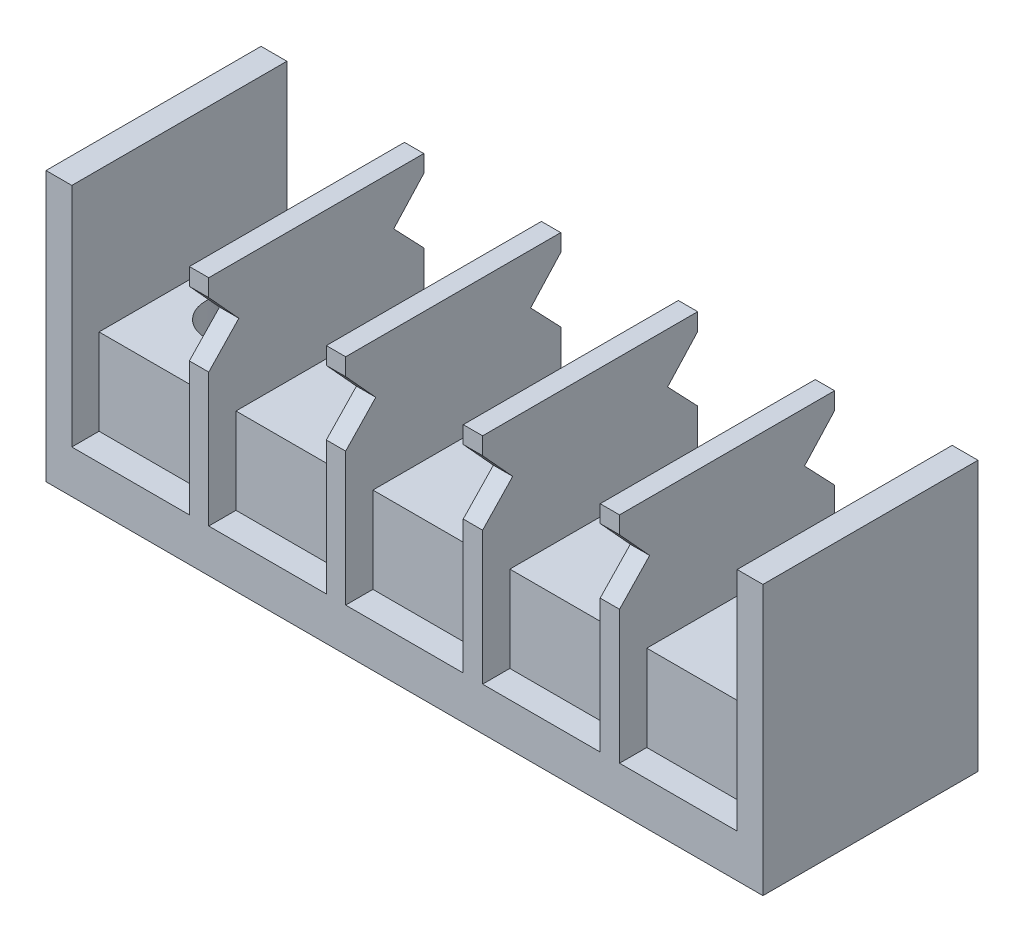
SolidWorks part; units mm, degrees
ref_plane "前视基准面" through (0, 0, 0) normal (0, 0, 1) x (1, 0, 0)
ref_plane "上视基准面" through (0, 0, 0) normal (0, 1, 0) x (1, 0, 0)
ref_plane "右视基准面" through (0, 0, 0) normal (1, 0, 0) x (0, 0, -1)
sketch "草图1" plane through (0, 0, 0) normal (0, 1, 0) x (1, 0, 0)
  line L0 (0, 12.7565) -> (0, -11.1323) construction
  line L1 (-25, -7.5) -> (25, -7.5)
  line L2 (-25, -7.5) -> (-25, 7.5)
  line L3 (-25, 7.5) -> (25, 7.5)
  line L4 (25, -7.5) -> (25, 7.5)
  line L5 (-29.1602, 0) -> (32.7116, 0) construction
  dimension "D1" = 50
  dimension "D2" = 15
extrude "拉伸1" add sketch "草图1" along normal blind 18.8
sketch "草图2" plane through (0, 18.8, 0) normal (0, 1, 0) x (-1, 0, 0)
  line L0 (-25, -7.5) -> (25, -7.5) construction
  line L1 (-23.2, -7.5) -> (23.2, -7.5)
  line L2 (-23.2, -7.5) -> (-23.2, 7.5)
  line L3 (-23.2, 7.5) -> (23.2, 7.5)
  line L4 (23.2, -7.5) -> (23.2, 7.5)
  line L5 (25, 7.5) -> (-25, 7.5) construction
  line L6 (-25, 7.5) -> (-25, -7.5) construction
  line L7 (25, -7.5) -> (25, 7.5) construction
  dimension "D1" = 1.8
  dimension "D2" = 1.8
extrude "切除-拉伸1" cut sketch "草图2" against normal offset from surface (0.8 mm away) 18 up to face at (0, 0, 0)
sketch "草图4" plane through (0, 18, 0) normal (0, 1, 0) x (-1, 0, 0)
  line L0 (23.2, 7.5) -> (-23.2, 7.5) construction
  line L1 (-23.2, -7.5) -> (-15, -7.5)
  line L2 (-23.2, -7.5) -> (-23.2, 7.5)
  line L3 (-23.2, 7.5) -> (-15, 7.5)
  line L4 (-15, -7.5) -> (-15, 7.5)
  line L5 (-13.65, -7.5) -> (-5.45, -7.5)
  line L6 (-13.65, -7.5) -> (-13.65, 7.5)
  line L7 (-13.65, 7.5) -> (-5.45, 7.5)
  line L8 (-5.45, -7.5) -> (-5.45, 7.5)
  line L9 (-4.1, -7.5) -> (4.1, -7.5)
  line L10 (-4.1, -7.5) -> (-4.1, 7.5)
  line L11 (-4.1, 7.5) -> (4.1, 7.5)
  line L12 (4.1, -7.5) -> (4.1, 7.5)
  line L13 (5.45, -7.5) -> (13.65, -7.5)
  line L14 (5.45, -7.5) -> (5.45, 7.5)
  line L15 (5.45, 7.5) -> (13.65, 7.5)
  line L16 (13.65, -7.5) -> (13.65, 7.5)
  line L17 (15, -7.5) -> (23.2, -7.5)
  line L18 (15, -7.5) -> (15, 7.5)
  line L19 (15, 7.5) -> (23.2, 7.5)
  line L20 (23.2, -7.5) -> (23.2, 7.5)
  dimension "D1" = 8.2
extrude "切除-拉伸2" cut sketch "草图4" against normal offset from surface (9 mm away) 9 up to face at (0, 0, 0)
sketch "草图5" plane through (0, 18, 0) normal (0, 1, 0) x (-1, 0, 0)
  line L0 (15, 7.5) -> (15, -7.5) construction
  line L1 (23.2, -7.5) -> (15, -7.5)
  line L2 (23.2, -7.5) -> (23.2, -5.6)
  line L3 (23.2, -5.6) -> (15, -5.6)
  line L4 (15, -7.5) -> (15, -5.6)
  line L5 (29.9336, 0) -> (-26.6321, 0) construction
  line L6 (15, 7.5) -> (15, 5.6)
  line L7 (23.2, 5.6) -> (15, 5.6)
  line L8 (23.2, 7.5) -> (23.2, 5.6)
  line L9 (23.2, 7.5) -> (15, 7.5)
  line L10 (13.65, -7.5) -> (5.45, -7.5)
  line L11 (13.65, -7.5) -> (13.65, -5.6)
  line L12 (13.65, -5.6) -> (5.45, -5.6)
  line L13 (5.45, -7.5) -> (5.45, -5.6)
  line L14 (5.45, 7.5) -> (5.45, 5.6)
  line L15 (13.65, 5.6) -> (5.45, 5.6)
  line L16 (13.65, 7.5) -> (13.65, 5.6)
  line L17 (13.65, 7.5) -> (5.45, 7.5)
  line L18 (4.1, -7.5) -> (-4.1, -7.5)
  line L19 (4.1, -7.5) -> (4.1, -5.6)
  line L20 (4.1, -5.6) -> (-4.1, -5.6)
  line L21 (-4.1, -7.5) -> (-4.1, -5.6)
  line L22 (-4.1, 7.5) -> (-4.1, 5.6)
  line L23 (4.1, 5.6) -> (-4.1, 5.6)
  line L24 (4.1, 7.5) -> (4.1, 5.6)
  line L25 (4.1, 7.5) -> (-4.1, 7.5)
  line L26 (-5.45, -7.5) -> (-13.65, -7.5)
  line L27 (-5.45, -7.5) -> (-5.45, -5.6)
  line L28 (-5.45, -5.6) -> (-13.65, -5.6)
  line L29 (-13.65, -7.5) -> (-13.65, -5.6)
  line L30 (-13.65, 7.5) -> (-13.65, 5.6)
  line L31 (-5.45, 5.6) -> (-13.65, 5.6)
  line L32 (-5.45, 7.5) -> (-5.45, 5.6)
  line L33 (-5.45, 7.5) -> (-13.65, 7.5)
  line L34 (-15, -7.5) -> (-23.2, -7.5)
  line L35 (-15, -7.5) -> (-15, -5.6)
  line L36 (-15, -5.6) -> (-23.2, -5.6)
  line L37 (-23.2, -7.5) -> (-23.2, -5.6)
  line L38 (-23.2, 7.5) -> (-23.2, 5.6)
  line L39 (-15, 5.6) -> (-23.2, 5.6)
  line L40 (-15, 7.5) -> (-15, 5.6)
  line L41 (-15, 7.5) -> (-23.2, 7.5)
  dimension "D1" = 11.2
extrude "切除-拉伸3" cut sketch "草图5" against normal offset from surface (15 mm away) 3 up to face at (0, 0, 0)
sketch "草图6" plane through (0, 0, 0) normal (0, -1, 0) x (1, 0, 0)
  line L0 (0, 12.0415) -> (0, -12.1791) construction
  line L1 (-6.3388, 0) -> (5.5048, 0) construction
  line L2 (0.75, 0.375) -> (-0.75, 0.375)
  line L3 (0.75, 0.375) -> (0.75, -0.375)
  line L4 (0.75, -0.375) -> (-0.75, -0.375)
  line L5 (-0.75, 0.375) -> (-0.75, -0.375)
  line L6 (10.3, 0.375) -> (8.8, 0.375)
  line L7 (10.3, 0.375) -> (10.3, -0.375)
  line L8 (10.3, -0.375) -> (8.8, -0.375)
  line L9 (8.8, 0.375) -> (8.8, -0.375)
  line L10 (0.75, 0.375) -> (10.3, 0.375) construction
  line L11 (-8.8, 0.375) -> (-8.8, -0.375)
  line L12 (-10.3, -0.375) -> (-8.8, -0.375)
  line L13 (-10.3, 0.375) -> (-10.3, -0.375)
  line L14 (-10.3, 0.375) -> (-8.8, 0.375)
  dimension "D1" = 0.75
  dimension "D2" = 1.5
  dimension "D3" = 9.55
extrude "拉伸2" add sketch "草图6" along normal blind 5.8
sketch "草图7" plane through (0, 9, 0) normal (0, 1, 0) x (-1, 0, 0)
  line L0 (0, -11.8563) -> (0, 13.0369) construction
  line L1 (-28.2468, 0) -> (30.271, 0) construction
  line L4 (-19.1, -9.8031) -> (-19.1, 12.0765) construction
  line L5 (-23.2, 5.6) -> (-23.2, -5.6) construction
  line L6 (-15, -5.6) -> (-15, 5.6) construction
  circle A0 centre (-19.1, 0) radius 2.25
  circle A1 centre (19.1, 0) radius 2.25
  dimension "D1" = 4.5
extrude "切除-拉伸4" cut sketch "草图7" against normal through all
sketch "草图8" plane through (15, 0, 0) normal (1, 0, 0) x (0, 0, -1)
  line L0 (7.5, 16.8) -> (5.4, 14.5)
  line L1 (5.4, 14.5) -> (7.5, 12.3)
  line L3 (7.5, 18) -> (-7.5, 18) construction
  line L4 (0, 21.7575) -> (0, -9.7526) construction
  line L6 (7.5, 18.8) -> (7.5, 0) construction
  line L8 (7.5, 16.8) -> (7.5, 12.3)
  line L9 (-7.5, 16.8) -> (-7.5, 12.3)
  line L10 (-5.4, 14.5) -> (-7.5, 12.3)
  line L11 (-7.5, 16.8) -> (-5.4, 14.5)
  dimension "D1" = 3.5
  dimension "D2" = 4.5
  dimension "D3" = 1.2
extrude "切除-拉伸5" cut sketch "草图8" against normal up to surface (38.2 mm away)
